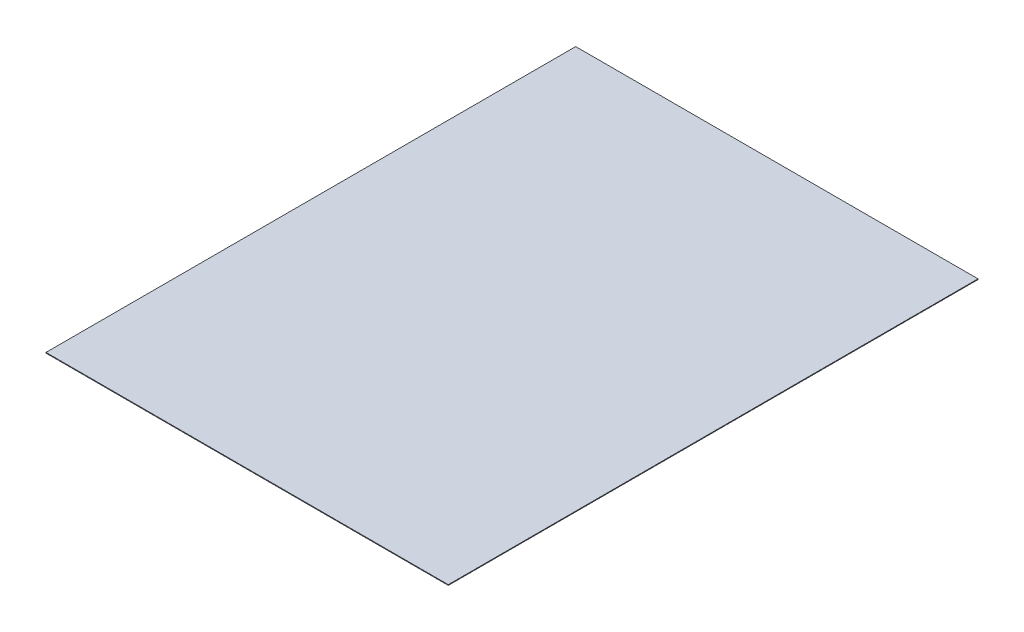
SolidWorks part; units mm, degrees
ref_plane "Front Plane" through (0, 0, 0) normal (0, 0, 1) x (1, 0, 0)
ref_plane "Top Plane" through (0, 0, 0) normal (0, 1, 0) x (1, 0, 0)
ref_plane "Right Plane" through (0, 0, 0) normal (1, 0, 0) x (0, 0, -1)
sketch "Esquisse1" plane through (0, 0, 0) normal (0, 1, 0) x (1, 0, 0)
  line L1 (-3000, 3950) -> (3000, 3950)
  line L2 (-3000, 3950) -> (-3000, -3950)
  line L3 (-3000, -3950) -> (3000, -3950)
  line L4 (3000, 3950) -> (3000, -3950)
  line L5 (-3000, 3950) -> (3000, -3950) construction
  line L6 (-3000, -3950) -> (3000, 3950) construction
  point P0 (0, 0)
extrude "Boss.-Extru.1" add sketch "Esquisse1" along normal blind 10
